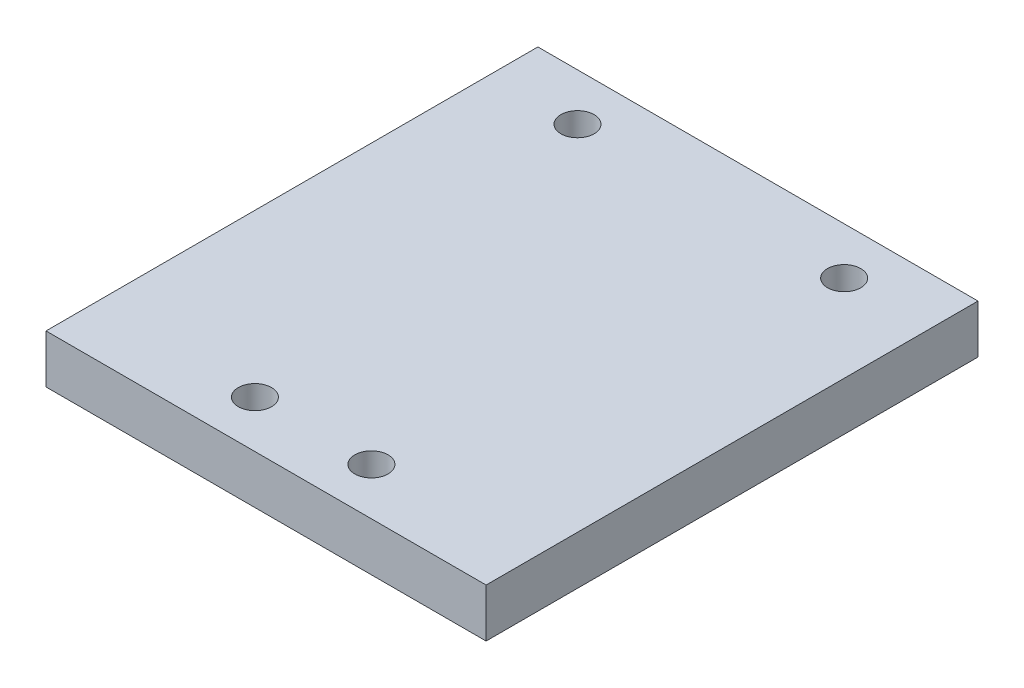
SolidWorks part; units mm, degrees
material "Nylon 6/10"
ref_plane "Front Plane" through (0, 0, 0) normal (0, 0, 1) x (1, 0, 0)
ref_plane "Top Plane" through (0, 0, 0) normal (0, 1, 0) x (1, 0, 0)
ref_plane "Right Plane" through (0, 0, 0) normal (1, 0, 0) x (0, 0, -1)
sketch "Sketch1" plane through (0, 0, 0) normal (0, 1, 0) x (1, 0, 0)
  line L1 (-21.59, -24.13) -> (21.59, -24.13)
  line L2 (-21.59, -24.13) -> (-21.59, 24.13)
  line L3 (-21.59, 24.13) -> (21.59, 24.13)
  line L4 (21.59, -24.13) -> (21.59, 24.13)
  line L5 (-21.59, -24.13) -> (21.59, 24.13) construction
  line L6 (-21.59, 24.13) -> (21.59, -24.13) construction
  point P0 (0, 0)
  dimension "D1" = 48.26
  dimension "D2" = 43.18
extrude "Base" add sketch "Sketch1" along normal blind 4.7625
hole_wizard "MotorHoles" positions "Sketch3" profile "Sketch2" counterbore size "#4" standard "ANSI Inch" end condition through all
sketch "Sketch3" plane through (0, 0, 0) normal (0, -1, 0) x (-1, 0, 0)
  line L2 (0, 0) -> (0, -31.1437) construction
  line L3 (0, 0) -> (28.6298, 0) construction
  point P0 (-5.715, -19.5072)
  point P2 (5.715, -19.5072)
  point P15 (13.081, 19.5072)
  point P17 (-13.081, 19.5072)
  dimension "D1" = 19.5072
  dimension "D2" = 11.43
  dimension "D3" = 39.0144
  dimension "D4" = 7.366
  dimension "D5" = 7.366
sketch "Sketch2" plane through (5.715, 0, 19.5072) normal (1, 0, 0) x (0, 0, -1)
  line L0 (0, 0) -> (0, 4.7625)
  line L1 (0, 4.7625) -> (1.632, 4.7625)
  line L3 (1.632, 4.7625) -> (1.6319, 1.7272)
  line L4 (3.3731, 1.7272) -> (1.6319, 1.7272)
  line L5 (3.3731, 1.7272) -> (3.3731, 0.635)
  line L6 (3.3731, 0.635) -> (4.0081, 0)
  line L7 (4.0081, 0) -> (0, 0)
  line L8 (-3.3731, 0.635) -> (-4.0081, 0) construction
  line L11 (0, -6.35) -> (0, 107.95) construction
  dimension "Thru Hole Dia." = 3.2639
  dimension "Thru Hole Depth" = 4.7625
  dimension "C'Bore Dia." = 6.7462
  dimension "C'Bore Depth" = 1.7272
  dimension "Near C'Sink Dia." = 8.0162
  dimension "Near C'Sink Angle" = 90
